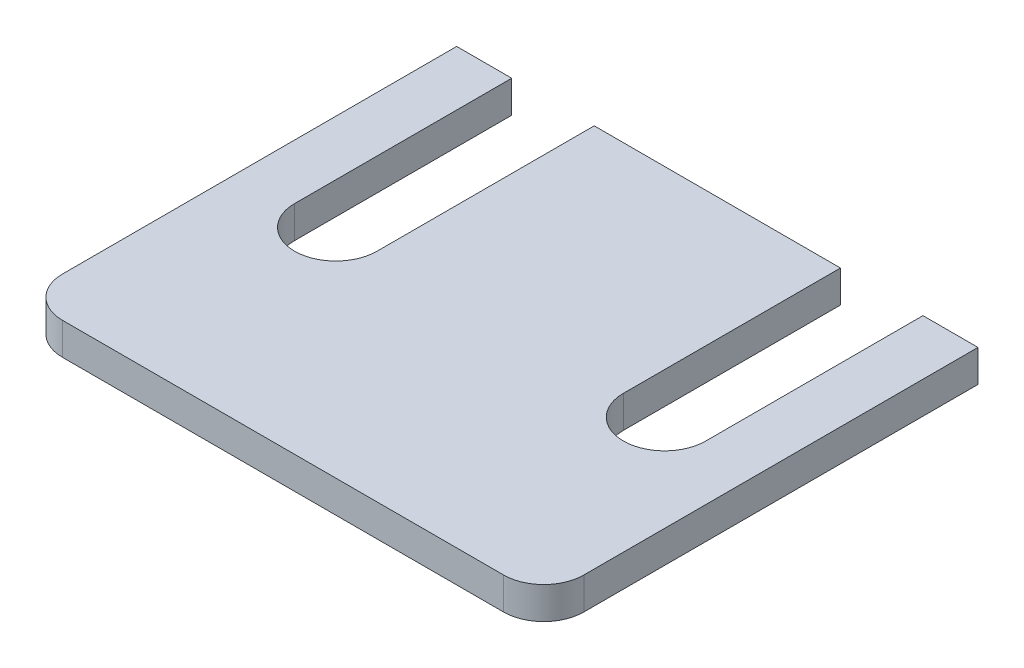
SolidWorks part; units mm, degrees
material "6061-T6 (SS)"
ref_plane "Front Plane" through (0, 0, 0) normal (0, 0, 1) x (1, 0, 0)
ref_plane "Top Plane" through (0, 0, 0) normal (0, 1, 0) x (1, 0, 0)
ref_plane "Right Plane" through (0, 0, 0) normal (1, 0, 0) x (0, 0, -1)
sketch "Sketch2" plane through (0, 0, 0) normal (0, 1, 0) x (1, 0, 0)
  line L0 (0, -3.9651) -> (0, 8.4579) construction
  line L1 (-20.6267, -17.1831) -> (20.6267, -17.1831)
  line L2 (-20.6267, -17.1831) -> (-20.6267, 17.1831)
  line L3 (-20.6267, 17.1831) -> (20.6267, 17.1831)
  line L4 (20.6267, -17.1831) -> (20.6267, 17.1831)
  line L5 (0, 0) -> (50000, 0) construction
  circle A0 centre (-13.0067, 0) radius 3.2639
  circle A1 centre (13.0067, 0) radius 3.2639
  dimension "D5" = 6.5278
  dimension "D6" = 7.62
  dimension "D1" = 41.2534
  dimension "D2" = 34.3662
  dimension "D3" = 20.6267
  dimension "D4" = 17.1831
extrude "Main Body" add sketch "Sketch2" along normal blind 2.54
fillet "Fillet1" radius 3.175 2 edges at (-20.6267, 1.27, 17.1831) (20.6267, 1.27, 17.1831)
sketch "Sketch3" plane through (0, 2.54, 0) normal (0, 1, 0) x (1, 0, 0)
  line L0 (-16.2706, 0) -> (-16.2706, 17.1831)
  line L1 (20.6267, 17.1831) -> (-20.6267, 17.1831) construction
  line L2 (-9.7428, 0) -> (-9.7428, 17.1831)
  line L3 (-9.7428, 17.1831) -> (-16.2706, 17.1831)
  line L4 (-16.2706, 0) -> (-9.7428, 0)
  line L5 (0, -1.397) -> (0, 1.397) construction
  line L6 (16.2706, 0) -> (16.2706, 17.1831)
  line L7 (9.7428, 17.1831) -> (16.2706, 17.1831)
  line L8 (9.7428, 0) -> (9.7428, 17.1831)
  line L9 (16.2706, 0) -> (9.7428, 0)
  circle A0 centre (-13.0067, 0) radius 3.2639 construction
extrude "Slots" cut sketch "Sketch3" against normal through all
